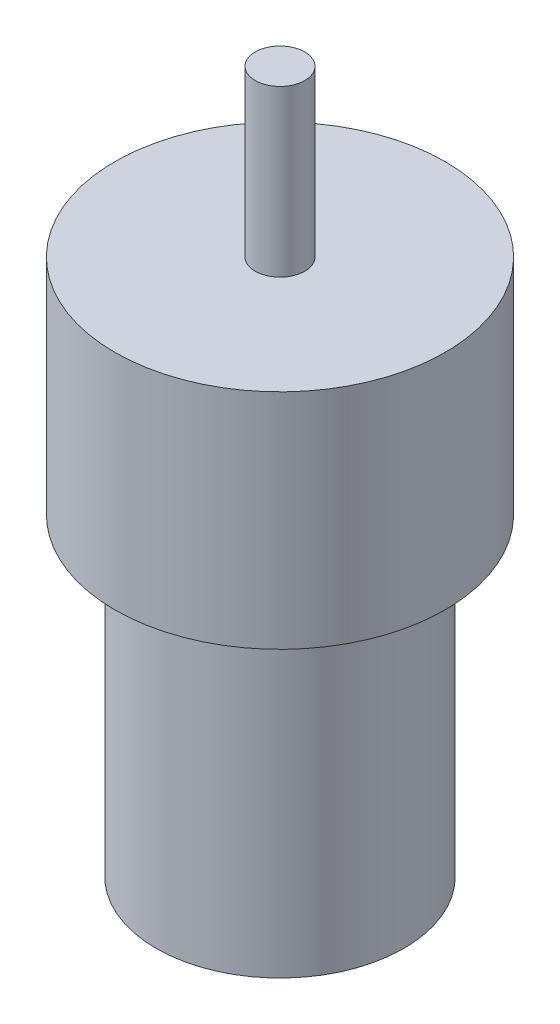
SolidWorks part; units mm, degrees
ref_plane "Front" through (0, 0, 0) normal (0, 0, 1) x (1, 0, 0)
ref_plane "Top" through (0, 0, 0) normal (0, 1, 0) x (1, 0, 0)
ref_plane "Right" through (0, 0, 0) normal (1, 0, 0) x (0, 0, -1)
sketch "Sketch1" plane through (0, 0, 0) normal (0, 0, 1) x (1, 0, 0)
  line L0 (0, 85) -> (0, 0)
  line L1 (0, 85) -> (3, 85)
  line L2 (3, 85) -> (3, 65)
  line L3 (3, 65) -> (20, 65)
  line L4 (20, 65) -> (20, 38)
  line L5 (0, 0) -> (15, 0)
  line L6 (15, 0) -> (15, 38)
  line L7 (15, 38) -> (20, 38)
  dimension "D1" = 85
  dimension "D2" = 3
  dimension "D3" = 20
  dimension "D4" = 20
  dimension "D5" = 27
  dimension "D6" = 15
revolve "Revolve1" add sketch "Sketch1" angle 360 about L0
